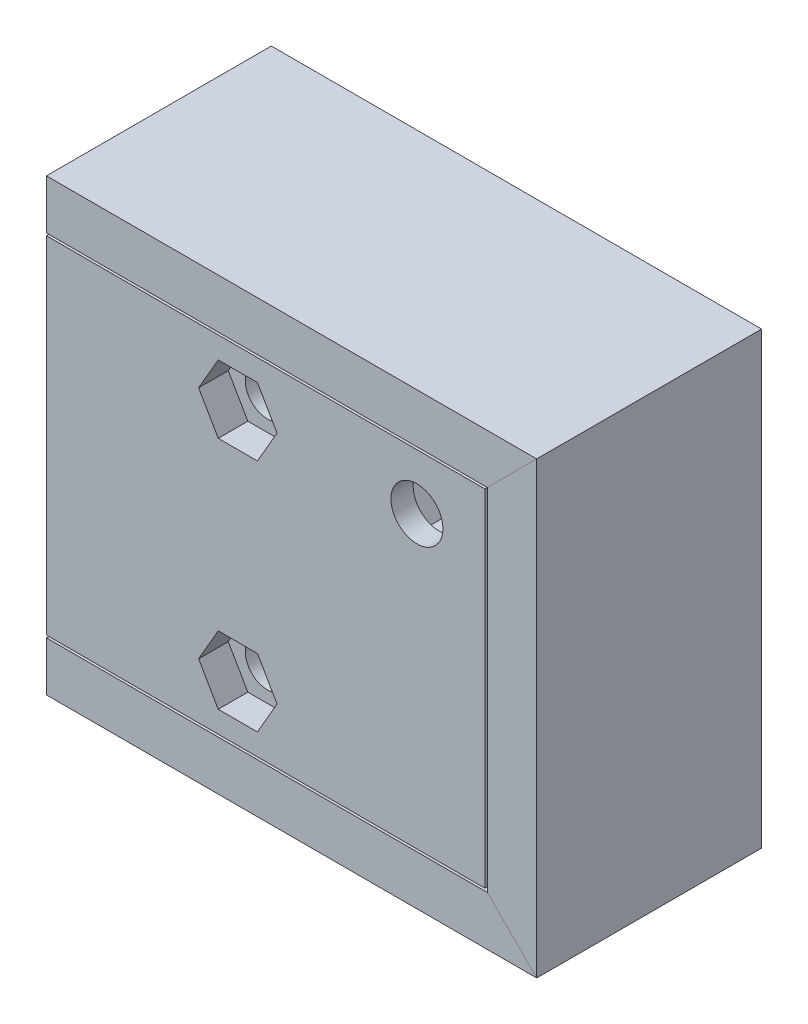
SolidWorks part; units mm, degrees
ref_plane "Front Plane" through (0, 0, 0) normal (0, 0, 1) x (1, 0, 0)
ref_plane "Top Plane" through (0, 0, 0) normal (0, 1, 0) x (1, 0, 0)
ref_plane "Right Plane" through (0, 0, 0) normal (1, 0, 0) x (0, 0, -1)
sketch "Sketch1" plane through (0, 0, 0) normal (0, 0, 1) x (1, 0, 0)
  line L0 (-1, 27) -> (-1, -1)
  line L1 (-1, -1) -> (34.5, -1)
  line L2 (34.5, -1) -> (34.5, 27)
  line L3 (34.5, 27) -> (-1, 27)
  line L4 (0, 26) -> (0, 0)
  line L5 (0, 0) -> (33.5, 0)
  line L6 (33.5, 0) -> (33.5, 26)
  line L7 (33.5, 26) -> (0, 26)
  line L8 (0, 26) -> (0, 0) construction
  line L9 (0, 0) -> (33.5, 0) construction
  line L10 (33.5, 0) -> (33.5, 26) construction
  line L11 (33.5, 26) -> (0, 26) construction
  line L12 (30.7321, 25.5) -> (27.2679, 25.5) construction
  line L13 (25.305, 22.5) -> (27.1525, 19.3)
  line L14 (27.1525, 19.3) -> (30.8475, 19.3)
  line L15 (30.8475, 19.3) -> (32.695, 22.5)
  line L16 (32.695, 22.5) -> (30.8475, 25.7)
  line L17 (30.8475, 25.7) -> (27.1525, 25.7)
  line L18 (27.1525, 25.7) -> (25.305, 22.5)
  line L19 (25.305, 3.45) -> (27.1525, 0.25)
  line L20 (27.1525, 0.25) -> (30.8475, 0.25)
  line L21 (30.8475, 0.25) -> (32.695, 3.45)
  line L22 (32.695, 3.45) -> (30.8475, 6.65)
  line L23 (30.8475, 6.65) -> (27.1525, 6.65)
  line L24 (27.1525, 6.65) -> (25.305, 3.45)
  circle A0 centre (29, 22.5) radius 3.2 construction
  circle A1 centre (29, 3.45) radius 3.2 construction
  circle A2 centre (14.5, 22.5) radius 1.8
  circle A3 centre (14.5, 3.5) radius 1.8
  circle A4 centre (14.5, 22.5) radius 1.6 construction
  dimension "D4" = 0.2
  dimension "D3" = 0.2
  dimension "D1" = 0
  dimension "D2" = 1
extrude "Boss-Extrude1" add sketch "Sketch1" along normal blind 5 contours L3 L0 L1 L2
sketch "Sketch2" plane through (0, 0, 5) normal (0, 0, 1) x (1, 0, 0)
  line L6 (25.305, 22.5) -> (27.1525, 19.3)
  line L7 (27.1525, 25.7) -> (25.305, 22.5)
  line L8 (30.8475, 25.7) -> (27.1525, 25.7)
  line L9 (32.695, 22.5) -> (30.8475, 25.7)
  line L10 (30.8475, 19.3) -> (32.695, 22.5)
  line L11 (27.1525, 19.3) -> (30.8475, 19.3)
  line L12 (25.305, 22.5) -> (27.1525, 19.3)
  line L13 (27.1525, 25.7) -> (25.305, 22.5)
  line L14 (30.8475, 25.7) -> (27.1525, 25.7)
  line L15 (32.695, 22.5) -> (30.8475, 25.7)
  line L16 (30.8475, 19.3) -> (32.695, 22.5)
  line L17 (27.1525, 19.3) -> (30.8475, 19.3)
  line L18 (25.305, 3.45) -> (27.1525, 0.25)
  line L19 (27.1525, 6.65) -> (25.305, 3.45)
  line L20 (30.8475, 6.65) -> (27.1525, 6.65)
  line L21 (32.695, 3.45) -> (30.8475, 6.65)
  line L22 (30.8475, 0.25) -> (32.695, 3.45)
  line L23 (27.1525, 0.25) -> (30.8475, 0.25)
  line L24 (25.305, 3.45) -> (27.1525, 0.25)
  line L25 (27.1525, 6.65) -> (25.305, 3.45)
  line L26 (30.8475, 6.65) -> (27.1525, 6.65)
  line L27 (32.695, 3.45) -> (30.8475, 6.65)
  line L28 (30.8475, 0.25) -> (32.695, 3.45)
  line L29 (27.1525, 0.25) -> (30.8475, 0.25)
  circle A0 centre (29, 22.5) radius 2.105
  circle A5 centre (29, 22.5) radius 1.905 construction
  dimension "D5" = 0.2
  dimension "D1" = 0
  dimension "D2" = 0
extrude "Boss-Extrude2" add sketch "Sketch2" against normal offset from surface (1.8 mm away) 0.2
sketch "Sketch3" plane through (0, 0, 5) normal (0, 0, 1) x (1, 0, 0)
  line L1 (11.3246, 22.5) -> (12.9123, 19.75)
  line L2 (12.9123, 19.75) -> (16.0877, 19.75)
  line L3 (16.0877, 19.75) -> (17.6754, 22.5)
  line L4 (17.6754, 22.5) -> (16.0877, 25.25)
  line L5 (16.0877, 25.25) -> (12.9123, 25.25)
  line L6 (12.9123, 25.25) -> (11.3246, 22.5)
  line L7 (11.3246, 3.5) -> (12.9123, 0.75)
  line L8 (12.9123, 0.75) -> (16.0877, 0.75)
  line L9 (16.0877, 0.75) -> (17.6754, 3.5)
  line L10 (17.6754, 3.5) -> (16.0877, 6.25)
  line L11 (16.0877, 6.25) -> (12.9123, 6.25)
  line L12 (12.9123, 6.25) -> (11.3246, 3.5)
  circle A0 centre (14.5, 22.5) radius 2.75 construction
  circle A1 centre (14.5, 3.5) radius 2.75 construction
  dimension "D1" = 5.5
extrude "Cut-Extrude1" cut sketch "Sketch3" against normal blind 2.4
sketch3d "3DSketch1"
  line L0 (-1, 27, 2.5) -> (34.5, 27, 2.5)
  line L1 (-1, 27, 5) -> (-1, 27, 0) construction
  line L2 (34.5, 27, 5) -> (34.5, 27, 0) construction
  line L3 (34.5, 27, 2.5) -> (34.5, -1, 2.5)
  line L4 (34.5, -1, 5) -> (34.5, -1, 0) construction
  line L5 (34.5, -1, 2.5) -> (-1, -1, 2.5)
  line L6 (-1, -1, 5) -> (-1, -1, 0) construction
sketch "Sketch4" plane through (-1, 0, 0) normal (-1, 0, 0) x (0, 0, 1)
  line L0 (2.5, 27) -> (1.5, 27)
  line L1 (5, 27) -> (0, 27) construction
  line L2 (1.5, 27) -> (1.5, 29)
  line L3 (1.5, 29) -> (3.5, 29)
  line L4 (3.5, 29) -> (3.5, 27)
  line L5 (3.5, 27) -> (2.5, 27)
  dimension "D1" = 2
  dimension "D2" = 2
sweep "Sweep1" add profiles "Sketch4" path "3DSketch1"
sketch "Sketch5" plane through (-1, 0, 0) normal (-1, 0, 0) x (0, 0, 1)
  line L0 (5, -1.2) -> (5, -5.2)
  line L1 (1.5, -1) -> (0, -1) construction
  line L2 (-13.2092, -5.2) -> (-13.2092, -3.2)
  line L3 (-13.2092, -3.2) -> (-11.2092, -1.2)
  line L4 (-11.2092, -1.2) -> (1.3, -1.2)
  line L7 (-13.2092, -1.2) -> (-13.2092, -5.2) construction
  line L8 (-13.2092, -5.2) -> (5, -5.2)
  line L9 (3.7, -1) -> (3.7, -3.2)
  line L10 (3.7, -3.2) -> (1.3, -3.2)
  line L11 (1.3, -3.2) -> (1.3, -1)
  line L12 (3.7, -1) -> (3.7, -3.2) construction
  line L13 (3.7, -3.2) -> (1.3, -3.2)
  line L14 (1.3, -3.2) -> (1.3, -1) construction
  line L15 (5, -5.2) -> (5, -1) construction
  line L17 (-11.7092, 14.7075) -> (-11.7092, 18.6946) construction
  line L18 (1.3, -1.2) -> (1.3, -3.2)
  line L19 (3.7, -1.2) -> (3.7, -3.2)
  line L20 (3.7, -1.2) -> (5, -1.2)
  line L21 (1.3, -1.2) -> (-13.2092, -1.2) construction
  line L23 (5, -1) -> (3.5, -1) construction
  dimension "D2" = 1.5
  dimension "D3" = 2
  dimension "D4" = 0.2
  dimension "D5" = 0.2
  dimension "D6" = 45
  dimension "D7" = 2
  dimension "D1" = 0.2
sketch3d "3DSketch2"
  line L0 (-1, -3, 2.5) -> (36.5, -3, 2.5)
  line L1 (-1, -3, 3.5) -> (-1, -3, 1.5) construction
  line L2 (36.5, -3, 1.5) -> (36.5, -3, 3.5) construction
  line L3 (36.5, -3, 2.5) -> (36.5, 29, 2.5)
  line L4 (36.5, 29, 1.5) -> (36.5, 29, 3.5) construction
  line L5 (36.5, 29, 2.5) -> (-1, 29, 2.5)
  line L6 (-1, 29, 3.5) -> (-1, 29, 1.5) construction
sweep "Sweep3" add profiles "Sketch5" path "3DSketch2"
